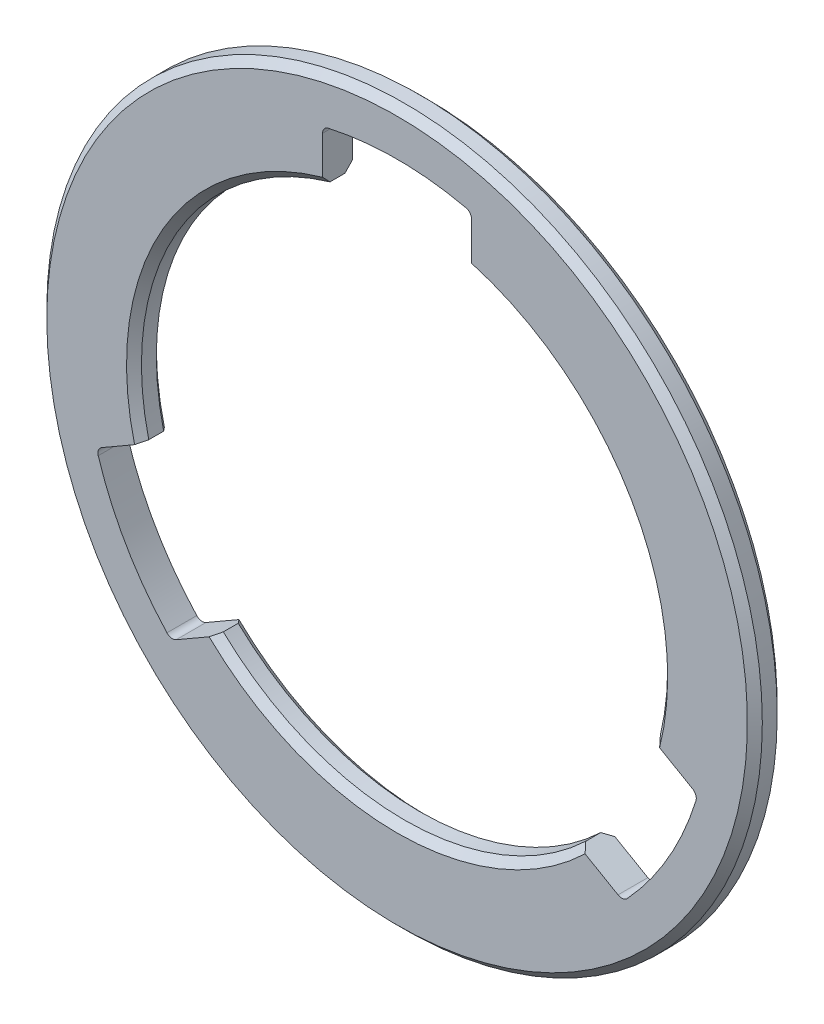
SolidWorks part; units mm, degrees
material "PET"
ref_plane "Front Plane" through (0, 0, 0) normal (0, 0, 1) x (1, 0, 0)
ref_plane "Top Plane" through (0, 0, 0) normal (0, 1, 0) x (1, 0, 0)
ref_plane "Right Plane" through (0, 0, 0) normal (1, 0, 0) x (0, 0, -1)
sketch "Sketch23" plane through (0, 0, 0) normal (0, 0, -1) x (-1, 0, 0)
  circle A2 centre (0, 0) radius 24
  circle A3 centre (0, 0) radius 17.5
extrude "Boss-Extrude3" add sketch "Sketch23" against normal blind 2 separate body
other "Move Face1" face at (-17.5, 0, 2) parameters "D1"=0.15
chamfer "Chamfer2" distance 0.5 angle 45 4 edges at (-17.65, 0, 2) (-17.65, 0, 0) (-24, 0, 0) (-24, 0, 2)
sketch "Sketch24" plane through (0, 0, 0) normal (0, 0, -1) x (-1, 0, 0)
  line L0 (-5, 20.3961) -> (-5, 16.927)
  line L1 (5, 20.3961) -> (5, 16.927)
  line L2 (0, 17.65) -> (0, 0) construction
  arc A0 (5, 20.3961) -> (-5, 20.3961) centre (0, 0) ccw
  arc A2 (5, 16.927) -> (-5, 16.927) centre (0, 0) ccw
  circle A3 centre (0, 0) radius 17.65 construction
  dimension "D2" = 21
  dimension "D1" = 10
extrude "Cut-Extrude3" cut sketch "Sketch24" against normal blind 2
fillet "Fillet1" radius 0.5 2 edges at (5, 20.3961, 1) (-5, 20.3961, 1)
pattern_circular "CirPattern1" count 3 over 360 about axis through (0, 0, 0) along (0, 0, 1) of "Cut-Extrude3", "Fillet1"
